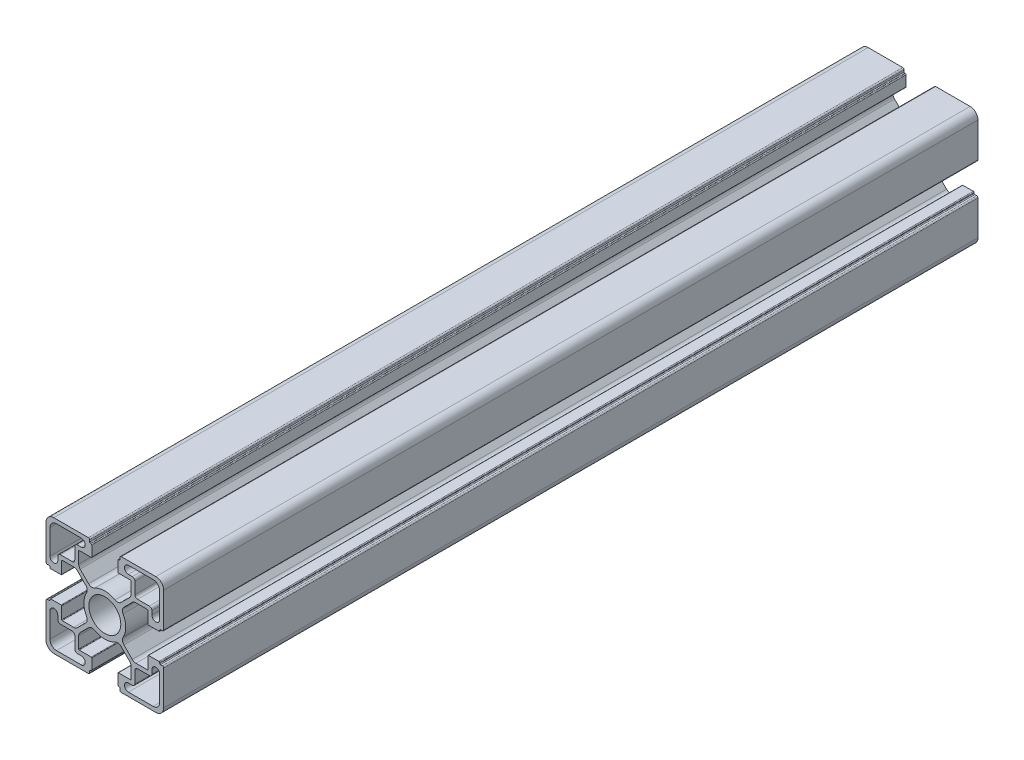
SolidWorks part; units mm, degrees
ref_plane "Front Plane" through (0, 0, 0) normal (0, 0, 1) x (1, 0, 0)
ref_plane "Top Plane" through (0, 0, 0) normal (0, 1, 0) x (1, 0, 0)
ref_plane "Right Plane" through (0, 0, 0) normal (1, 0, 0) x (0, 0, -1)
sketch "Sketch1" plane through (0, 0, 0) normal (0, 0, 1) x (1, 0, 0)
  line L3 (-22.5, 19.5) -> (-22.5, 6.3)
  line L4 (-20.7, 5) -> (-16.7, 5)
  line L5 (-16.5, 5.2) -> (-16.5, 9.8)
  line L6 (-16.3, 10) -> (-11.8642, 10)
  line L7 (-10.4924, 9.4318) -> (-7.2967, 6.236)
  line L8 (-21, 18.5) -> (-21, 9)
  line L9 (-16.5, 5) -> (-16.5, 10) construction
  line L10 (-18, 9) -> (-18, 10.5)
  line L11 (-17, 11.5) -> (-12.5, 11.5)
  line L12 (-22, 5.8) -> (-21.3, 5.8)
  line L13 (-21, 5.5) -> (-21, 5.3)
  line L14 (-21, 22.5) -> (-21, 6.5) construction
  line L15 (-18, 11.5) -> (-10.4393, 11.5) construction
  line L16 (-10.4393, 11.5) -> (-5.1016, 6.1623) construction
  line L17 (-18, 6.5) -> (-18, 11.5) construction
  line L18 (-22.5, 22.5) -> (-22.5, 5) construction
  line L19 (-22.5, 5) -> (-16.5, 5) construction
  line L20 (-21, 6.5) -> (-18, 6.5) construction
  line L21 (-16.5, 10) -> (-11.0607, 10) construction
  line L22 (-11.0607, 10) -> (-6.1623, 5.1016) construction
  line L23 (-5.5, 21) -> (-5.3, 21)
  line L24 (-5.8, 22) -> (-5.8, 21.3)
  line L25 (-11.5, 17) -> (-11.5, 12.5)
  line L26 (-9, 18) -> (-10.5, 18)
  line L27 (-18.5, 21) -> (-9, 21)
  line L28 (-9.4318, 10.4924) -> (-6.236, 7.2967)
  line L29 (-10, 16.3) -> (-10, 11.8642)
  line L30 (-5.2, 16.5) -> (-9.8, 16.5)
  line L31 (-5, 20.7) -> (-5, 16.7)
  line L32 (-19.5, 22.5) -> (-6.3, 22.5)
  line L33 (19.5, 22.5) -> (6.3, 22.5)
  line L34 (5, 20.7) -> (5, 16.7)
  line L35 (5.2, 16.5) -> (9.8, 16.5)
  line L36 (10, 16.3) -> (10, 11.8642)
  line L37 (9.4318, 10.4924) -> (6.236, 7.2967)
  line L38 (18.5, 21) -> (9, 21)
  line L39 (9, 18) -> (10.5, 18)
  line L40 (11.5, 17) -> (11.5, 12.5)
  line L41 (5.8, 22) -> (5.8, 21.3)
  line L42 (5.5, 21) -> (5.3, 21)
  line L43 (21, 5.5) -> (21, 5.3)
  line L44 (22, 5.8) -> (21.3, 5.8)
  line L45 (17, 11.5) -> (12.5, 11.5)
  line L46 (18, 9) -> (18, 10.5)
  line L47 (21, 18.5) -> (21, 9)
  line L48 (10.4924, 9.4318) -> (7.2967, 6.236)
  line L49 (16.3, 10) -> (11.8642, 10)
  line L50 (16.5, 5.2) -> (16.5, 9.8)
  line L51 (20.7, 5) -> (16.7, 5)
  line L52 (22.5, 19.5) -> (22.5, 6.3)
  line L53 (22.5, -19.5) -> (22.5, -6.3)
  line L54 (20.7, -5) -> (16.7, -5)
  line L55 (16.5, -5.2) -> (16.5, -9.8)
  line L56 (16.3, -10) -> (11.8642, -10)
  line L57 (10.4924, -9.4318) -> (7.2967, -6.236)
  line L58 (21, -18.5) -> (21, -9)
  line L59 (18, -9) -> (18, -10.5)
  line L60 (17, -11.5) -> (12.5, -11.5)
  line L61 (22, -5.8) -> (21.3, -5.8)
  line L62 (21, -5.5) -> (21, -5.3)
  line L63 (5.5, -21) -> (5.3, -21)
  line L64 (5.8, -22) -> (5.8, -21.3)
  line L65 (11.5, -17) -> (11.5, -12.5)
  line L66 (9, -18) -> (10.5, -18)
  line L67 (18.5, -21) -> (9, -21)
  line L68 (9.4318, -10.4924) -> (6.236, -7.2967)
  line L69 (10, -16.3) -> (10, -11.8642)
  line L70 (5.2, -16.5) -> (9.8, -16.5)
  line L71 (5, -20.7) -> (5, -16.7)
  line L72 (19.5, -22.5) -> (6.3, -22.5)
  line L73 (-19.5, -22.5) -> (-6.3, -22.5)
  line L74 (-5, -20.7) -> (-5, -16.7)
  line L75 (-5.2, -16.5) -> (-9.8, -16.5)
  line L76 (-10, -16.3) -> (-10, -11.8642)
  line L77 (-9.4318, -10.4924) -> (-6.236, -7.2967)
  line L78 (-18.5, -21) -> (-9, -21)
  line L79 (-9, -18) -> (-10.5, -18)
  line L80 (-11.5, -17) -> (-11.5, -12.5)
  line L81 (-5.8, -22) -> (-5.8, -21.3)
  line L82 (-5.5, -21) -> (-5.3, -21)
  line L83 (-21, -5.5) -> (-21, -5.3)
  line L84 (-22, -5.8) -> (-21.3, -5.8)
  line L85 (-17, -11.5) -> (-12.5, -11.5)
  line L86 (-18, -9) -> (-18, -10.5)
  line L87 (-21, -18.5) -> (-21, -9)
  line L88 (-10.4924, -9.4318) -> (-7.2967, -6.236)
  line L89 (-16.3, -10) -> (-11.8642, -10)
  line L90 (-16.5, -5.2) -> (-16.5, -9.8)
  line L91 (-20.7, -5) -> (-16.7, -5)
  line L92 (-22.5, -19.5) -> (-22.5, -6.3)
  arc A0 (0, 6.1) -> (-6.1, 0) centre (0, 0) ccw
  arc A1 (-6.9766, 3.9149) -> (-8, 0) centre (0, 0) ccw
  arc A2 (-21, 9) -> (-18, 9) centre (-19.5, 9) ccw
  arc A3 (-22, 5.8) -> (-22.5, 6.3) centre (-22, 6.3) cw
  arc A4 (-21, 5.3) -> (-20.7, 5) centre (-20.7, 5.3) ccw
  arc A5 (-21.3, 5.8) -> (-21, 5.5) centre (-21.3, 5.5) cw
  arc A6 (-16.7, 5) -> (-16.5, 5.2) centre (-16.7, 5.2) ccw
  arc A7 (-16.5, 9.8) -> (-16.3, 10) centre (-16.3, 9.8) cw
  arc A8 (-7.2967, 6.236) -> (-6.9766, 3.9149) centre (-8.6685, 4.8643) cw
  arc A9 (-11.8642, 10) -> (-10.4924, 9.4318) centre (-11.8642, 8.06) cw
  arc A10 (-18, 10.5) -> (-17, 11.5) centre (-17, 10.5) cw
  arc A11 (-10.5, 18) -> (-11.5, 17) centre (-10.5, 17) ccw
  arc A12 (-10, 11.8642) -> (-9.4318, 10.4924) centre (-8.06, 11.8642) ccw
  arc A13 (-6.236, 7.2967) -> (-3.9149, 6.9766) centre (-4.8643, 8.6685) ccw
  arc A14 (-9.8, 16.5) -> (-10, 16.3) centre (-9.8, 16.3) ccw
  arc A15 (-5, 16.7) -> (-5.2, 16.5) centre (-5.2, 16.7) cw
  arc A16 (-5.8, 21.3) -> (-5.5, 21) centre (-5.5, 21.3) ccw
  arc A17 (-5.3, 21) -> (-5, 20.7) centre (-5.3, 20.7) cw
  arc A18 (-5.8, 22) -> (-6.3, 22.5) centre (-6.3, 22) ccw
  arc A19 (-9, 21) -> (-9, 18) centre (-9, 19.5) cw
  arc A20 (-3.9149, 6.9766) -> (0, 8) centre (0, 0) cw
  arc A21 (-21, 18.5) -> (-18.5, 21) centre (-18.5, 18.5) cw
  arc A22 (-22.5, 19.5) -> (-19.5, 22.5) centre (-19.5, 19.5) cw
  arc A23 (-12.5, 11.5) -> (-11.5, 12.5) centre (-12.5, 12.5) ccw
  arc A24 (6.1, 0) -> (0, 6.1) centre (0, 0) ccw
  arc A25 (3.9149, 6.9766) -> (0, 8) centre (0, 0) ccw
  arc A26 (9, 21) -> (9, 18) centre (9, 19.5) ccw
  arc A27 (5.8, 22) -> (6.3, 22.5) centre (6.3, 22) cw
  arc A28 (5.3, 21) -> (5, 20.7) centre (5.3, 20.7) ccw
  arc A29 (5.8, 21.3) -> (5.5, 21) centre (5.5, 21.3) cw
  arc A30 (5, 16.7) -> (5.2, 16.5) centre (5.2, 16.7) ccw
  arc A31 (9.8, 16.5) -> (10, 16.3) centre (9.8, 16.3) cw
  arc A32 (6.236, 7.2967) -> (3.9149, 6.9766) centre (4.8643, 8.6685) cw
  arc A33 (10, 11.8642) -> (9.4318, 10.4924) centre (8.06, 11.8642) cw
  arc A34 (10.5, 18) -> (11.5, 17) centre (10.5, 17) cw
  arc A35 (18, 10.5) -> (17, 11.5) centre (17, 10.5) ccw
  arc A36 (11.8642, 10) -> (10.4924, 9.4318) centre (11.8642, 8.06) ccw
  arc A37 (7.2967, 6.236) -> (6.9766, 3.9149) centre (8.6685, 4.8643) ccw
  arc A38 (16.5, 9.8) -> (16.3, 10) centre (16.3, 9.8) ccw
  arc A39 (16.7, 5) -> (16.5, 5.2) centre (16.7, 5.2) cw
  arc A40 (21.3, 5.8) -> (21, 5.5) centre (21.3, 5.5) ccw
  arc A41 (21, 5.3) -> (20.7, 5) centre (20.7, 5.3) cw
  arc A42 (22, 5.8) -> (22.5, 6.3) centre (22, 6.3) ccw
  arc A43 (21, 9) -> (18, 9) centre (19.5, 9) cw
  arc A44 (6.9766, 3.9149) -> (8, 0) centre (0, 0) cw
  arc A45 (18.5, 21) -> (21, 18.5) centre (18.5, 18.5) cw
  arc A46 (19.5, 22.5) -> (22.5, 19.5) centre (19.5, 19.5) cw
  arc A47 (11.5, 12.5) -> (12.5, 11.5) centre (12.5, 12.5) ccw
  arc A48 (0, -6.1) -> (6.1, 0) centre (0, 0) ccw
  arc A49 (6.9766, -3.9149) -> (8, 0) centre (0, 0) ccw
  arc A50 (21, -9) -> (18, -9) centre (19.5, -9) ccw
  arc A51 (22, -5.8) -> (22.5, -6.3) centre (22, -6.3) cw
  arc A52 (21, -5.3) -> (20.7, -5) centre (20.7, -5.3) ccw
  arc A53 (21.3, -5.8) -> (21, -5.5) centre (21.3, -5.5) cw
  arc A54 (16.7, -5) -> (16.5, -5.2) centre (16.7, -5.2) ccw
  arc A55 (16.5, -9.8) -> (16.3, -10) centre (16.3, -9.8) cw
  arc A56 (7.2967, -6.236) -> (6.9766, -3.9149) centre (8.6685, -4.8643) cw
  arc A57 (11.8642, -10) -> (10.4924, -9.4318) centre (11.8642, -8.06) cw
  arc A58 (18, -10.5) -> (17, -11.5) centre (17, -10.5) cw
  arc A59 (10.5, -18) -> (11.5, -17) centre (10.5, -17) ccw
  arc A60 (10, -11.8642) -> (9.4318, -10.4924) centre (8.06, -11.8642) ccw
  arc A61 (6.236, -7.2967) -> (3.9149, -6.9766) centre (4.8643, -8.6685) ccw
  arc A62 (9.8, -16.5) -> (10, -16.3) centre (9.8, -16.3) ccw
  arc A63 (5, -16.7) -> (5.2, -16.5) centre (5.2, -16.7) cw
  arc A64 (5.8, -21.3) -> (5.5, -21) centre (5.5, -21.3) ccw
  arc A65 (5.3, -21) -> (5, -20.7) centre (5.3, -20.7) cw
  arc A66 (5.8, -22) -> (6.3, -22.5) centre (6.3, -22) ccw
  arc A67 (9, -21) -> (9, -18) centre (9, -19.5) cw
  arc A68 (3.9149, -6.9766) -> (0, -8) centre (0, 0) cw
  arc A69 (21, -18.5) -> (18.5, -21) centre (18.5, -18.5) cw
  arc A70 (22.5, -19.5) -> (19.5, -22.5) centre (19.5, -19.5) cw
  arc A71 (12.5, -11.5) -> (11.5, -12.5) centre (12.5, -12.5) ccw
  arc A72 (-6.1, 0) -> (0, -6.1) centre (0, 0) ccw
  arc A73 (-3.9149, -6.9766) -> (0, -8) centre (0, 0) ccw
  arc A74 (-9, -21) -> (-9, -18) centre (-9, -19.5) ccw
  arc A75 (-5.8, -22) -> (-6.3, -22.5) centre (-6.3, -22) cw
  arc A76 (-5.3, -21) -> (-5, -20.7) centre (-5.3, -20.7) ccw
  arc A77 (-5.8, -21.3) -> (-5.5, -21) centre (-5.5, -21.3) cw
  arc A78 (-5, -16.7) -> (-5.2, -16.5) centre (-5.2, -16.7) ccw
  arc A79 (-9.8, -16.5) -> (-10, -16.3) centre (-9.8, -16.3) cw
  arc A80 (-6.236, -7.2967) -> (-3.9149, -6.9766) centre (-4.8643, -8.6685) cw
  arc A81 (-10, -11.8642) -> (-9.4318, -10.4924) centre (-8.06, -11.8642) cw
  arc A82 (-10.5, -18) -> (-11.5, -17) centre (-10.5, -17) cw
  arc A83 (-18, -10.5) -> (-17, -11.5) centre (-17, -10.5) ccw
  arc A84 (-11.8642, -10) -> (-10.4924, -9.4318) centre (-11.8642, -8.06) ccw
  arc A85 (-7.2967, -6.236) -> (-6.9766, -3.9149) centre (-8.6685, -4.8643) ccw
  arc A86 (-16.5, -9.8) -> (-16.3, -10) centre (-16.3, -9.8) ccw
  arc A87 (-16.7, -5) -> (-16.5, -5.2) centre (-16.7, -5.2) cw
  arc A88 (-21.3, -5.8) -> (-21, -5.5) centre (-21.3, -5.5) ccw
  arc A89 (-21, -5.3) -> (-20.7, -5) centre (-20.7, -5.3) cw
  arc A90 (-22, -5.8) -> (-22.5, -6.3) centre (-22, -6.3) ccw
  arc A91 (-21, -9) -> (-18, -9) centre (-19.5, -9) cw
  arc A92 (-6.9766, -3.9149) -> (-8, 0) centre (0, 0) cw
  arc A93 (-18.5, -21) -> (-21, -18.5) centre (-18.5, -18.5) cw
  arc A94 (-19.5, -22.5) -> (-22.5, -19.5) centre (-19.5, -19.5) cw
  arc A95 (-11.5, -12.5) -> (-12.5, -11.5) centre (-12.5, -12.5) ccw
  point P24 (-5.8, 21)
  point P32 (-22.5, 5.8)
  point P35 (-21, 5)
  point P38 (-21, 5.8)
  point P83 (-5, 21)
  point P84 (-5.8, 22.5)
  point P87 (-21, 21)
  point P93 (-11.5, 11.5)
  point P102 (21, 5.8)
  point P158 (21, 5)
  point P159 (22.5, 5.8)
  point P172 (5.8, -21)
  point P228 (5, -21)
  point P229 (5.8, -22.5)
  point P242 (-21, -5.8)
  point P298 (-21, -5)
  point P299 (-22.5, -5.8)
  dimension "D11" = 0.5
  dimension "D12" = 0.3
  dimension "D13" = 0.2
  dimension "D14" = 0.2
  dimension "D6" = 1.94
  dimension "D15" = 1
  dimension "D16" = 2.5
  dimension "D4" = 3
  dimension "D17" = 1
  dimension "D5" = 0.8
  dimension "D7" = 1.5
  dimension "D9" = 1.5
  dimension "D10" = 4
  dimension "D18" = 4
extrude "Boss-Extrude1" add sketch "Sketch1" along normal blind 311.4557
scale "Scale1" scale about centroid uniform scaling yes scale factor 0.564444
